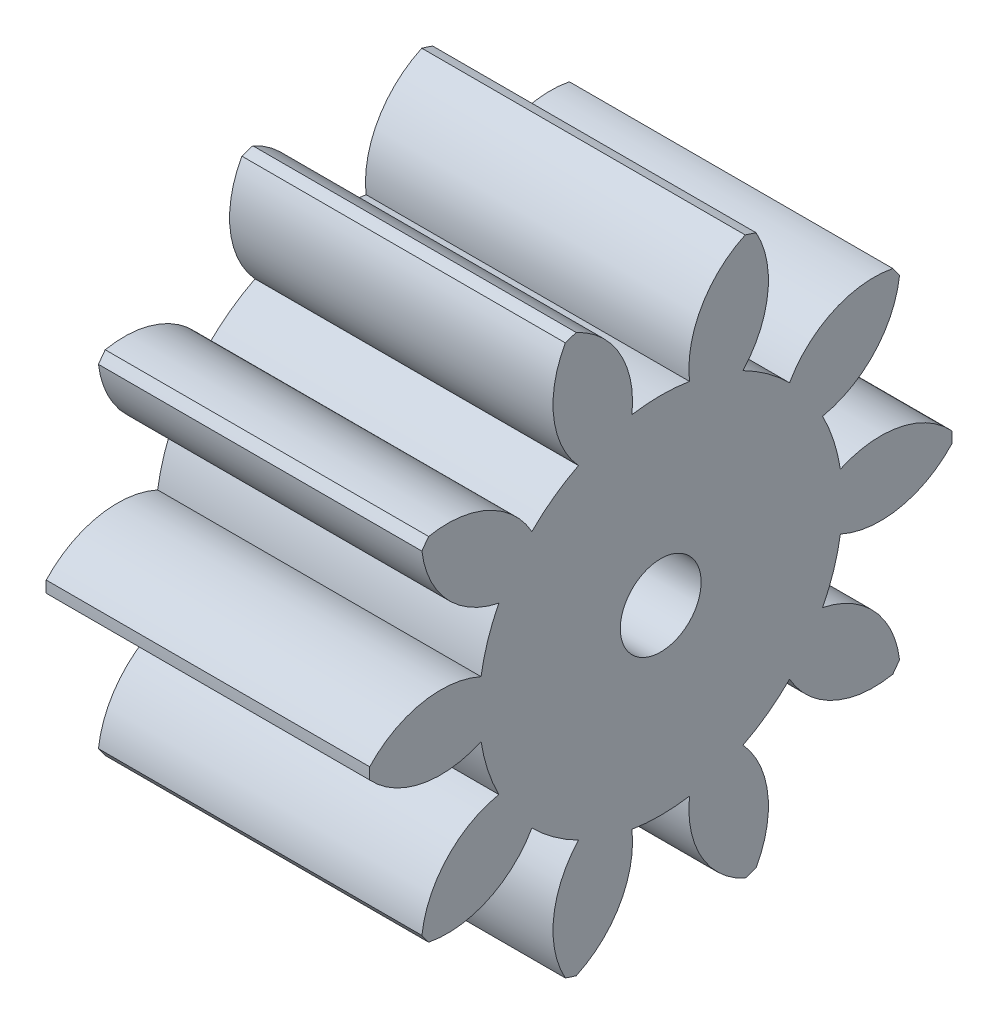
SolidWorks part; units mm, degrees
ref_plane "Plane1" through (0, 0, 0) normal (0, 0, 1) x (1, 0, 0)
ref_plane "Plane2" through (0, 0, 0) normal (0, 1, 0) x (1, 0, 0)
ref_plane "Plane3" through (0, 0, 0) normal (1, 0, 0) x (0, 0, -1)
other "Configuration Table"
sketch "HoldingSke" plane through (0, 0, 0) normal (0, 1, 0) x (1, 0, 0)
  line L0 (0, 0) -> (1.6413, -0.2894)
  line L1 (-15, 0) -> (100, 0) construction
  line L2 (0, 0) -> (-2.1039, 2.3779)
  line L3 (0, 0) -> (-11.863, 4.5341)
  line L4 (0, 0) -> (8.5048, 1.4996)
  line L5 (0, 0) -> (-46.8476, -17.4728)
  line L6 (0, 0) -> (-3.3159, -2.2372)
  line L7 (-2.1039, 2.3779) -> (8.6586, 51.2059)
  line L8 (-76.2, 54.61) -> (-76.1, 54.61)
  line L9 (-71.009, 38.7566) -> (-53.1078, 45.2721)
  line L10 (-76.2, 71.12) -> (104.1128, 71.12)
  line L11 (0, 0) -> (-4, 0)
  line L12 (-76.2, 101.6) -> (-76.177, 101.6)
  line L13 (24.9733, 27.94) -> (52.9518, 28.4284)
  line L14 (24.9733, 27.94) -> (24.9743, 27.94)
  line L15 (24.9733, 27.94) -> (100.4006, 29.5858)
  line L16 (-63.627, -0.6) -> (-12.827, -0.6)
  circle A0 centre (0, 0) radius 0.5
  circle A1 centre (0, 0) radius 2.249
  circle A2 centre (0, 0) radius 37.5
  circle A3 centre (0, 0) radius 0.5
  dimension "MHD" = 4.498
  dimension "Hub_dia" = 75
  dimension "Bore" = 1
  dimension "MBD" = 1
  dimension "Num_teeth" = 10
  dimension "Pitch" = 1.6667
  dimension "Overall_len" = 50
  dimension "Show_teeth" = 10
  dimension "Thickness" = 4
  dimension "OAL" = 50.0001
  dimension "T_dim" = 0.1
  dimension "Ap" = 20
  dimension "H" = 19.05
  dimension "Pitch_radius" = 180.3128
  dimension "Width" = 4
  dimension "Backlash" = 0.023
  dimension "Addendum_fac" = 1
  dimension "Dedendum_fac" = 1.25
  dimension "Clearance_fac" = 0.25
  dimension "Dedendum_add" = 0.001
  dimension "Module" = 0.6
sketch "BasProSke" plane through (0, 0, 0) normal (0, 1, 0) x (1, 0, 0)
  line L0 (-10, 0) -> (60, 0) construction
  line L1 (0, 0) -> (0, 3.6)
  line L2 (0, 0) -> (4, 0)
  line L3 (4, 0) -> (4, 3.6)
  line L4 (4, 3.6) -> (0, 3.6)
  dimension "Thickness" = 4
  dimension "Diameter" = 7.2
revolve "Base-Revolve" add sketch "BasProSke" angle 360 about L0
sketch "TooCutSke" plane through (0, 0, 0) normal (1, 0, 0) x (0, 0, -1)
  line L1 (0, 0) -> (0, 107) construction
  line L2 (0, 0) -> (-0.5095, 2.9564) construction
  line L3 (0, 0) -> (-1.835, 5.6477) construction
  line L4 (-0.5095, 2.9564) -> (-0.9175, 2.8238) construction
  arc A0 (0.356, 2.2206) -> (-0.356, 2.2206) centre (0, 0) ccw
  arc A1 (1.0802, 3.4607) -> (-1.0802, 3.4607) centre (0, 0) ccw
  circle A2 centre (0, 0) radius 3 construction
  circle A3 centre (0, 0) radius 2.8191 construction
  arc A4 (-0.356, 2.2206) -> (-1.0802, 3.4607) centre (-1.5483, 2.3558) ccw
  arc A5 (1.0802, 3.4607) -> (0.356, 2.2206) centre (1.5483, 2.3558) ccw
  dimension "Root_dia" = 4.498
  dimension "Overcut_dia" = 7.2508
  dimension "Pitch_dia" = 6
  dimension "Base_dia" = 5.6382
  dimension "Flank_rad" = 1.2
  dimension "Half_ang" = 18
  dimension "Half_CT" = 0.4291
extrude "ToothCut" cut sketch "TooCutSke" along normal through all
fillet "Breaks" [suppressed] radius 0.012
fillet "RootFillets" [suppressed] radius 0.151
pattern_circular "TeethCuts" count 10 every 36 about axis through (-10, 0, 0) along (1, 0, 0) of "ToothCut", "RootFillets", "Breaks"
sketch "HubNeaOneSke" plane through (0, 0, 0) normal (-1, 0, 0) x (0, 0, 1)
  circle A0 centre (0, 0) radius 2.249
  dimension "Diameter" = 4.498
extrude "HubNearOne" [suppressed] add sketch "HubNeaOneSke" along normal blind 46.0001
sketch "HubNeaBotSke" plane through (0, 0, 0) normal (-1, 0, 0) x (0, 0, 1)
  circle A0 centre (0, 0) radius 2.249
  dimension "Diameter" = 4.498
extrude "HubNearBoth" [suppressed] add sketch "HubNeaBotSke" along normal blind 23
ref_plane "FarPln" through (4, 0, 0) normal (1, 0, 0) x (0, 0, -1)
sketch "HubFarSke" plane through (4, 0, 0) normal (1, 0, 0) x (0, 0, -1)
  circle A0 centre (0, 0) radius 2.249
  dimension "Diameter" = 4.498
extrude "HubFar" [suppressed] add sketch "HubFarSke" along normal blind 23
sketch "BorSke" plane through (0, 0, 0) normal (1, 0, 0) x (0, 0, -1)
  circle A0 centre (0, 0) radius 0.5
  dimension "Diameter" = 1
extrude "Bore" cut sketch "BorSke" along normal mid plane 100.0001
sketch "KeySke" plane through (0, 0, 0) normal (1, 0, 0) x (0, 0, -1)
  line L0 (-0.05, 0) -> (-0.05, 0.6)
  line L1 (-0.05, 0.6) -> (0.05, 0.6)
  line L2 (0.05, 0.6) -> (0.05, 0)
  line L3 (0, 0) -> (0, 34) construction
  line L4 (-0.05, 0) -> (0.05, 0)
  dimension "Offset" = 0.6
  dimension "Width" = 0.1
extrude "Keyway" [suppressed] cut sketch "KeySke" along normal mid plane 100.0001
pattern_circular "Keyway2" [suppressed] count 2 every 90 about axis through (-10, 0, 0) along (1, 0, 0)
equation "' \"Module@HoldingSke\" = 6.35"
equation "' \"Num_teeth@HoldingSke\" = 12"
equation "' \"Ap@HoldingSke\" =  20"
equation "' \"Ap@HoldingSke\" = 20"
equation "' \"Width@HoldingSke\" = 0.5 * 25.4"
equation "' \"Hub_dia@HoldingSke\"= 1 * 25.4"
equation "' \"Hub_dia@HoldingSke\" = 1 * 25.4"
equation "' \"Overall_len@HoldingSke\" = 1.0 * 25.4"
equation "' \"Bore@HoldingSke\" = 0.75 * 25.4"
equation "' \"T_dim@HoldingSke\" = 0.1 * 25.4"
equation "' \"Width@KeySke\" = 0.25 * 25.4"
equation "' \"Show_teeth@HoldingSke\" = 13"
equation "' \"Backlash@HoldingSke\" = 0.009 * 25.4"
equation "' \"Addendum_fac@HoldingSke\" = 1.0"
equation "' \"Dedendum_fac@HoldingSke\" = 1.25"
equation "' \"Dedendum_add@HoldingSke\" = 0.00005 * 25.4"
equation "' \"Clearance_fac@HoldingSke\" = 0.25"
equation "\"Pitch@HoldingSke\" = 1 / \"Module@HoldingSke\""
equation "\"Overcut_dia@TooCutSke\" = (\"Num_teeth@HoldingSke\" + 2 * \"Addendum_fac@HoldingSke\") / \"Pitch@HoldingSke\" + 0.002 * 25.4"
equation "\"Pitch_dia@TooCutSke\" = \"Num_teeth@HoldingSke\" / \"Pitch@HoldingSke\""
equation "\"Base_dia@TooCutSke\" = \"Num_teeth@HoldingSke\" / \"Pitch@HoldingSke\" * cos((\"Ap@HoldingSke\"  * 3.14159265 / 180))"
equation "\"Root_dia@TooCutSke\" = (\"Num_teeth@HoldingSke\" + 2) / \"Pitch@HoldingSke\" - 2 * (\"Addendum_fac@HoldingSke\" + \"Dedendum_fac@HoldingSke\") / \"Pitch@HoldingSke\" - \"Dedendum_add@HoldingSke\" * 2"
equation "\"Half_ang@TooCutSke\" = 180 / \"Num_teeth@HoldingSke\""
equation "\"Half_CT@TooCutSke\" = \"Num_teeth@HoldingSke\" / \"Pitch@HoldingSke\" * sin((3.14159265 / 2 / \"Num_teeth@HoldingSke\")) / 2 - 7 * \"Backlash@HoldingSke\" / 4"
equation "\"Flank_rad@TooCutSke\" = \"Num_teeth@HoldingSke\" / \"Pitch@HoldingSke\" / 5"
equation "\"Radius@RootFillets\" = \"Clearance_fac@HoldingSke\" / \"Pitch@HoldingSke\" + \"Dedendum_add@HoldingSke\""
equation "\"Break_rad@Breaks\" = 0.02 / \"Pitch@HoldingSke\""
equation "\"Thickness@HoldingSke\" = \"Width@HoldingSke\""
equation "\"OAL@HoldingSke\" = \"Thickness@HoldingSke\""
equation "\"MHD@HoldingSke\" = (\"Num_teeth@HoldingSke\" + 2) / \"Pitch@HoldingSke\" - 2 * (\"Addendum_fac@HoldingSke\" + \"Dedendum_fac@HoldingSke\")  / \"Pitch@HoldingSke\" - \"Dedendum_add@HoldingSke\" * 2"
equation "\"MBD@HoldingSke\" = (\"Num_teeth@HoldingSke\" + 2) / \"Pitch@HoldingSke\" - 2 * (\"Addendum_fac@HoldingSke\" + \"Dedendum_fac@HoldingSke\")  / \"Pitch@HoldingSke\" - \"Dedendum_add@HoldingSke\" * 2 - 0.002 * 25.4"
equation "\"MHD@HoldingSke\" = ((sgn( \"MHD@HoldingSke\" - \"Hub_dia@HoldingSke\" )-1)*( \"MHD@HoldingSke\" - \"Hub_dia@HoldingSke\" ))/-2+ \"Hub_dia@HoldingSke\""
equation "\"MBD@HoldingSke\" = ((sgn( \"MBD@HoldingSke\" - \"Bore@HoldingSke\" )-1)*( \"MBD@HoldingSke\" - \"Bore@HoldingSke\" ))/-2+ \"Bore@HoldingSke\""
equation "\"OAL@HoldingSke\" = ((sgn( \"OAL@HoldingSke\" - \"Overall_len@HoldingSke\" )+1)*( \"OAL@HoldingSke\" - \"Overall_len@HoldingSke\" ))/2 + \"Overall_len@HoldingSke\" + 0.000002 * 25.4"
equation "\"Num_teeth@TeethCuts\" = int( \"Show_teeth@HoldingSke\" ) + 1"
equation "\"Num_teeth@TeethCuts\" = ((sgn( \"Num_teeth@TeethCuts\" - \"Num_teeth@HoldingSke\" )-1)*( \"Num_teeth@TeethCuts\" - \"Num_teeth@HoldingSke\" ))/-2+ \"Num_teeth@HoldingSke\""
equation "\"Num_teeth@TeethCuts\" = ((sgn( \"Num_teeth@TeethCuts\" - 2.0)+1)*( \"Num_teeth@TeethCuts\" - 2.0))/2 +2.0"
equation "\"Angle@TeethCuts\" = 360.0 / \"Num_teeth@HoldingSke\""
equation "\"Diameter@BasProSke\" = (\"Num_teeth@HoldingSke\" + 2 * \"Addendum_fac@HoldingSke\") / \"Pitch@HoldingSke\""
equation "\"Thickness@BasProSke\"  = \"Thickness@HoldingSke\""
equation "' \"Fillet_rad@BasProSke\" =  \"Thickness@HoldingSke\" * 0.05"
equation "' \"Fillet_rad@BasProSke\" = \"Thickness@HoldingSke\" * 0.05"
equation "\"MHD@HoldingSke\" = ((sgn( \"MHD@HoldingSke\" - \"Root_dia@TooCutSke\" )-1)*( \"MHD@HoldingSke\" - \"Root_dia@TooCutSke\" ))/-2+ \"Root_dia@TooCutSke\""
equation "\"Diameter@HubNeaOneSke\" = \"MHD@HoldingSke\""
equation "\"Length@HubNearOne\" = \"OAL@HoldingSke\" - \"Thickness@BasProSke\""
equation "\"Diameter@HubNeaBotSke\" = \"MHD@HoldingSke\""
equation "\"Length@HubNearBoth\" = ( \"OAL@HoldingSke\" - \"Thickness@BasProSke\" ) / 2.0"
equation "\"Thickness@FarPln\" = \"Thickness@BasProSke\""
equation "\"Diameter@HubFarSke\" = \"MHD@HoldingSke\""
equation "\"Length@HubFar\" = ( \"OAL@HoldingSke\" - \"Thickness@BasProSke\" ) / 2.0"
equation "\"Diameter@BorSke\" = \"MBD@HoldingSke\""
equation "\"D1@Bore\" = \"OAL@HoldingSke\" * 2.0"
equation "\"D1@Keyway\" = \"OAL@HoldingSke\" * 2.0"
equation "\"Offset@KeySke\" = \"T_dim@HoldingSke\" + \"MBD@HoldingSke\" / 2.0"
